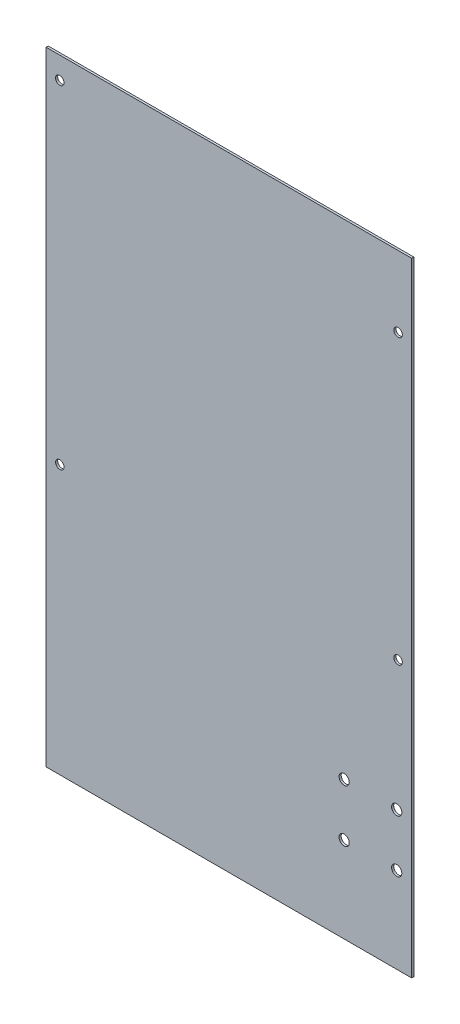
SolidWorks part; units mm, degrees
material "CA"
ref_plane "Alzado" through (0, 0, 0) normal (0, 0, 1) x (1, 0, 0)
ref_plane "Planta" through (0, 0, 0) normal (0, 1, 0) x (1, 0, 0)
ref_plane "Vista lateral" through (0, 0, 0) normal (1, 0, 0) x (0, 0, -1)
sketch "Croquis1" plane through (0, 0, 0) normal (0, 0, 1) x (1, 0, 0)
  line L1 (85.09, -145.09) -> (-85.09, -145.09)
  line L2 (85.09, -145.09) -> (85.09, 145.09)
  line L3 (85.09, 145.09) -> (-85.09, 145.09)
  line L4 (-85.09, -145.09) -> (-85.09, 145.09)
  line L5 (85.09, -145.09) -> (-85.09, 145.09) construction
  line L6 (85.09, 145.09) -> (-85.09, -145.09) construction
  point P0 (0, 0)
  dimension "D1" = 170.18
  dimension "D2" = 290.18
extrude "Saliente-Extruir1" add sketch "Croquis1" along normal blind 1
sketch "Croquis2" plane through (0, 0, 0) normal (0, 0, -1) x (-1, 0, 0)
  line L0 (85.09, 145.09) -> (78.74, 145.09) construction
  line L2 (-85.09, 145.09) -> (85.09, 145.09) construction
  line L3 (78.74, 145.09) -> (78.74, 134.91) construction
  line L4 (0, 145.09) -> (0, -138.734) construction
  line L5 (-78.74, 145.09) -> (-78.74, 112.07) construction
  line L6 (-85.09, 145.0247) -> (-78.74, 145.09) construction
  line L7 (0, 0) -> (102.0316, 0) construction
  line L8 (85.09, 145.09) -> (85.09, -20.01) construction
  line L9 (85.09, 145.09) -> (85.09, -145.09) construction
  line L10 (85.09, -20.01) -> (78.74, -20.01) construction
  line L11 (-85.09, -20.01) -> (-78.74, -20.01) construction
  circle A1 centre (-78.74, 112.07) radius 1.975
  circle A2 centre (78.74, 134.91) radius 1.975
  circle A5 centre (78.74, -20.01) radius 1.975
  circle A6 centre (-78.74, -20.01) radius 1.975
  dimension "D3" = 3.95
  dimension "D6" = 3.95
  dimension "D1" = 6.35
  dimension "D2" = 10.18
  dimension "D4" = 165.1
  dimension "D5" = 6.35
extrude "Cortar-Extruir1" cut sketch "Croquis2" against normal blind 1
sketch "Croquis3" plane through (0, 0, 0) normal (0, 0, -1) x (-1, 0, 0)
  line L6 (0, 145.09) -> (0, -52.4227) construction
  line L7 (-85.09, 145.09) -> (85.09, 145.09) construction
  line L8 (-53.64, -105.2) -> (-78.11, -105.2) construction
  line L9 (-53.64, -80.73) -> (-53.64, -105.2) construction
  line L10 (-78.11, -80.73) -> (-53.64, -80.73) construction
  line L11 (-85.09, -80.73) -> (-78.11, -80.73) construction
  line L12 (-85.09, 145.09) -> (-85.09, -80.73) construction
  circle A4 centre (-78.11, -105.2) radius 2.38
  circle A5 centre (-53.64, -105.2) radius 2.38
  circle A6 centre (-53.64, -80.73) radius 2.38
  circle A7 centre (-78.11, -80.73) radius 2.38
extrude "Cortar-Extruir2" cut sketch "Croquis3" against normal blind 10
